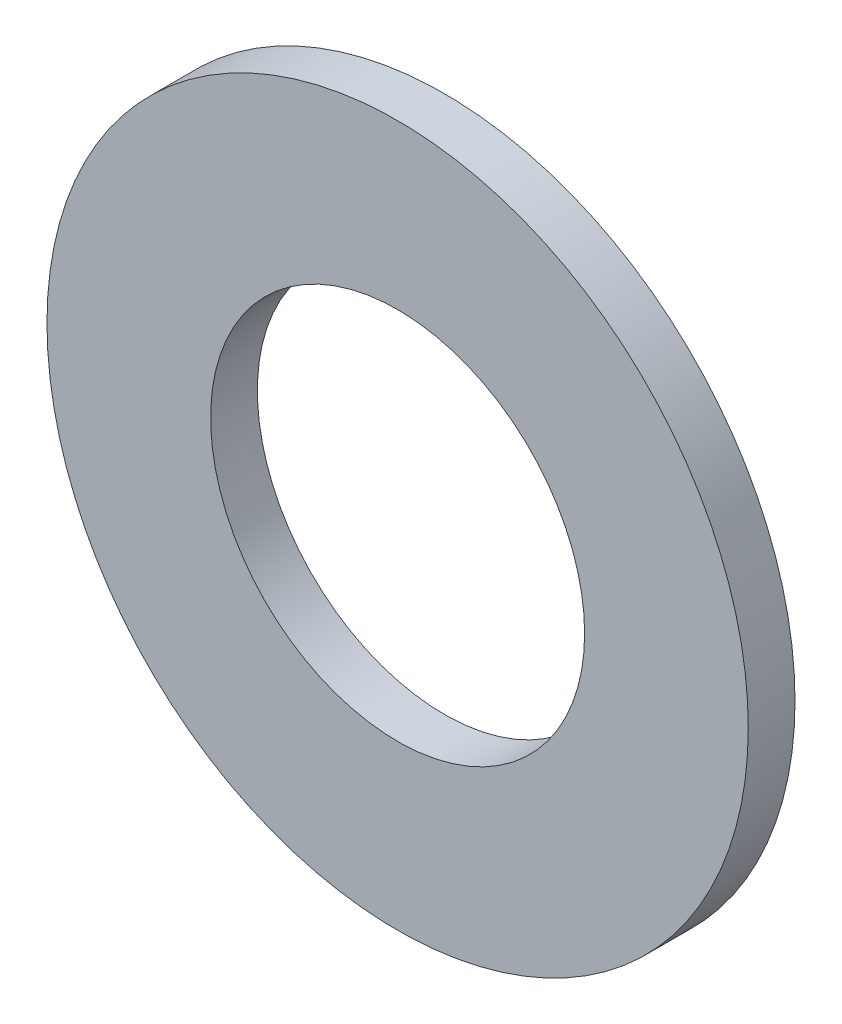
SolidWorks part; units mm, degrees
ref_plane "Plan de face" through (0, 0, 0) normal (0, 0, 1) x (1, 0, 0)
ref_plane "Plan de dessus" through (0, 0, 0) normal (0, 1, 0) x (1, 0, 0)
ref_plane "Plan de droite" through (0, 0, 0) normal (1, 0, 0) x (0, 0, -1)
sketch "Esquisse1" plane through (0, 0, 0) normal (0, 0, 1) x (1, 0, 0)
  circle A0 centre (-17.2664, 15.5767) radius 7.5
  circle A1 centre (-17.2664, 15.5767) radius 4
  dimension "D1" = 8
  dimension "D2" = 15
extrude "Boss.-Extru.1" add sketch "Esquisse1" along normal blind 1
